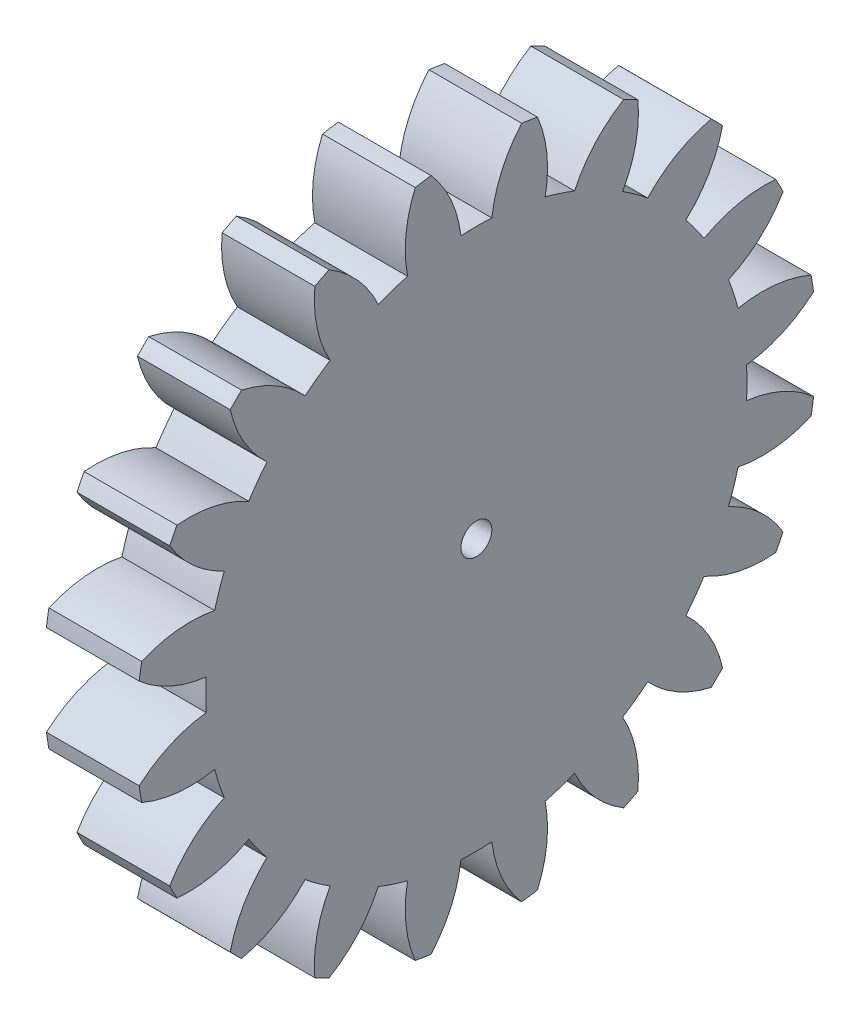
SolidWorks part; units mm, degrees
ref_plane "Plane1" through (0, 0, 0) normal (0, 0, 1) x (1, 0, 0)
ref_plane "Plane2" through (0, 0, 0) normal (0, 1, 0) x (1, 0, 0)
ref_plane "Plane3" through (0, 0, 0) normal (1, 0, 0) x (0, 0, -1)
other "Configuration Table"
sketch "HoldingSke" plane through (0, 0, 0) normal (0, 1, 0) x (1, 0, 0)
  line L0 (0, 0) -> (0.9397, -0.342)
  line L1 (-15, 0) -> (100, 0) construction
  line L2 (0, 0) -> (-2.1039, 2.3779)
  line L3 (0, 0) -> (-11.863, 4.5341)
  line L4 (0, 0) -> (8.1152, 2.9537)
  line L5 (0, 0) -> (-46.8476, -17.4728)
  line L6 (0, 0) -> (-2.4869, -1.6779)
  line L7 (-2.1039, 2.3779) -> (8.6586, 51.2059)
  line L8 (-76.2, 54.61) -> (-76.1, 54.61)
  line L9 (-71.009, 38.7566) -> (-53.1078, 45.2721)
  line L10 (-76.2, 71.12) -> (104.1128, 71.12)
  line L11 (0, 0) -> (-3, 0)
  line L12 (-76.2, 101.6) -> (-76.162, 101.6)
  line L13 (24.9733, 27.94) -> (52.9518, 28.4284)
  line L14 (24.9733, 27.94) -> (24.9743, 27.94)
  line L15 (24.9733, 27.94) -> (100.4006, 29.5858)
  line L16 (-63.627, -1) -> (-12.827, -1)
  circle A0 centre (0, 0) radius 0.5
  circle A1 centre (0, 0) radius 8.749
  circle A2 centre (0, 0) radius 37.5
  circle A3 centre (0, 0) radius 0.5
  dimension "MHD" = 17.498
  dimension "Hub_dia" = 75
  dimension "Bore" = 1
  dimension "MBD" = 1
  dimension "Num_teeth" = 20
  dimension "Pitch" = 1
  dimension "Overall_len" = 50
  dimension "Show_teeth" = 20
  dimension "Thickness" = 3
  dimension "OAL" = 50.0001
  dimension "T_dim" = 0.1
  dimension "Ap" = 20
  dimension "H" = 19.05
  dimension "Pitch_radius" = 180.3128
  dimension "Width" = 3
  dimension "Backlash" = 0.038
  dimension "Addendum_fac" = 1
  dimension "Dedendum_fac" = 1.25
  dimension "Clearance_fac" = 0.25
  dimension "Dedendum_add" = 0.001
  dimension "Module" = 1
sketch "BasProSke" plane through (0, 0, 0) normal (0, 1, 0) x (1, 0, 0)
  line L0 (-10, 0) -> (60, 0) construction
  line L1 (0, 0) -> (0, 11)
  line L2 (0, 0) -> (3, 0)
  line L3 (3, 0) -> (3, 11)
  line L4 (3, 11) -> (0, 11)
  dimension "Thickness" = 3
  dimension "Diameter" = 22
revolve "Base-Revolve" add sketch "BasProSke" angle 360 about L0
sketch "TooCutSke" plane through (0, 0, 0) normal (1, 0, 0) x (0, 0, -1)
  line L1 (0, 0) -> (0, 107) construction
  line L2 (0, 0) -> (-0.8511, 9.9637) construction
  line L3 (0, 0) -> (-3.1206, 19.7028) construction
  line L4 (-0.8511, 9.9637) -> (-1.5603, 9.8514) construction
  arc A0 (0.4999, 8.7347) -> (-0.4999, 8.7347) centre (0, 0) ccw
  arc A1 (1.4852, 10.9249) -> (-1.4852, 10.9249) centre (0, 0) ccw
  circle A2 centre (0, 0) radius 10 construction
  circle A3 centre (0, 0) radius 9.3969 construction
  arc A4 (-0.4999, 8.7347) -> (-1.4852, 10.9249) centre (-4.4722, 8.2645) ccw
  arc A5 (1.4852, 10.9249) -> (0.4999, 8.7347) centre (4.4722, 8.2645) ccw
  dimension "Root_dia" = 17.498
  dimension "Overcut_dia" = 22.0508
  dimension "Pitch_dia" = 20
  dimension "Base_dia" = 18.7939
  dimension "Flank_rad" = 4
  dimension "Half_ang" = 9
  dimension "Half_CT" = 0.7181
extrude "ToothCut" cut sketch "TooCutSke" along normal through all
fillet "Breaks" [suppressed] radius 0.02
fillet "RootFillets" [suppressed] radius 0.251
pattern_circular "TeethCuts" count 20 every 18 about axis through (-10, 0, 0) along (1, 0, 0) of "ToothCut", "RootFillets", "Breaks"
sketch "HubNeaOneSke" plane through (0, 0, 0) normal (-1, 0, 0) x (0, 0, 1)
  circle A0 centre (0, 0) radius 8.749
  dimension "Diameter" = 17.498
extrude "HubNearOne" [suppressed] add sketch "HubNeaOneSke" along normal blind 47.0001
sketch "HubNeaBotSke" plane through (0, 0, 0) normal (-1, 0, 0) x (0, 0, 1)
  circle A0 centre (0, 0) radius 8.749
  dimension "Diameter" = 17.498
extrude "HubNearBoth" [suppressed] add sketch "HubNeaBotSke" along normal blind 23.5
ref_plane "FarPln" through (3, 0, 0) normal (1, 0, 0) x (0, 0, -1)
sketch "HubFarSke" plane through (3, 0, 0) normal (1, 0, 0) x (0, 0, -1)
  circle A0 centre (0, 0) radius 8.749
  dimension "Diameter" = 17.498
extrude "HubFar" [suppressed] add sketch "HubFarSke" along normal blind 23.5
sketch "BorSke" plane through (0, 0, 0) normal (1, 0, 0) x (0, 0, -1)
  circle A0 centre (0, 0) radius 0.5
  dimension "Diameter" = 1
extrude "Bore" cut sketch "BorSke" along normal mid plane 100.0001
sketch "KeySke" plane through (0, 0, 0) normal (1, 0, 0) x (0, 0, -1)
  line L0 (-0.05, 0) -> (-0.05, 0.6)
  line L1 (-0.05, 0.6) -> (0.05, 0.6)
  line L2 (0.05, 0.6) -> (0.05, 0)
  line L3 (0, 0) -> (0, 34) construction
  line L4 (-0.05, 0) -> (0.05, 0)
  dimension "Offset" = 0.6
  dimension "Width" = 0.1
extrude "Keyway" [suppressed] cut sketch "KeySke" along normal mid plane 100.0001
pattern_circular "Keyway2" [suppressed] count 2 every 90 about axis through (-10, 0, 0) along (1, 0, 0)
equation "' \"Module@HoldingSke\" = 6.35"
equation "' \"Num_teeth@HoldingSke\" = 12"
equation "' \"Ap@HoldingSke\" =  20"
equation "' \"Ap@HoldingSke\" = 20"
equation "' \"Width@HoldingSke\" = 0.5 * 25.4"
equation "' \"Hub_dia@HoldingSke\"= 1 * 25.4"
equation "' \"Hub_dia@HoldingSke\" = 1 * 25.4"
equation "' \"Overall_len@HoldingSke\" = 1.0 * 25.4"
equation "' \"Bore@HoldingSke\" = 0.75 * 25.4"
equation "' \"T_dim@HoldingSke\" = 0.1 * 25.4"
equation "' \"Width@KeySke\" = 0.25 * 25.4"
equation "' \"Show_teeth@HoldingSke\" = 13"
equation "' \"Backlash@HoldingSke\" = 0.009 * 25.4"
equation "' \"Addendum_fac@HoldingSke\" = 1.0"
equation "' \"Dedendum_fac@HoldingSke\" = 1.25"
equation "' \"Dedendum_add@HoldingSke\" = 0.00005 * 25.4"
equation "' \"Clearance_fac@HoldingSke\" = 0.25"
equation "\"Pitch@HoldingSke\" = 1 / \"Module@HoldingSke\""
equation "\"Overcut_dia@TooCutSke\" = (\"Num_teeth@HoldingSke\" + 2 * \"Addendum_fac@HoldingSke\") / \"Pitch@HoldingSke\" + 0.002 * 25.4"
equation "\"Pitch_dia@TooCutSke\" = \"Num_teeth@HoldingSke\" / \"Pitch@HoldingSke\""
equation "\"Base_dia@TooCutSke\" = \"Num_teeth@HoldingSke\" / \"Pitch@HoldingSke\" * cos((\"Ap@HoldingSke\"  * 3.14159265 / 180))"
equation "\"Root_dia@TooCutSke\" = (\"Num_teeth@HoldingSke\" + 2) / \"Pitch@HoldingSke\" - 2 * (\"Addendum_fac@HoldingSke\" + \"Dedendum_fac@HoldingSke\") / \"Pitch@HoldingSke\" - \"Dedendum_add@HoldingSke\" * 2"
equation "\"Half_ang@TooCutSke\" = 180 / \"Num_teeth@HoldingSke\""
equation "\"Half_CT@TooCutSke\" = \"Num_teeth@HoldingSke\" / \"Pitch@HoldingSke\" * sin((3.14159265 / 2 / \"Num_teeth@HoldingSke\")) / 2 - 7 * \"Backlash@HoldingSke\" / 4"
equation "\"Flank_rad@TooCutSke\" = \"Num_teeth@HoldingSke\" / \"Pitch@HoldingSke\" / 5"
equation "\"Radius@RootFillets\" = \"Clearance_fac@HoldingSke\" / \"Pitch@HoldingSke\" + \"Dedendum_add@HoldingSke\""
equation "\"Break_rad@Breaks\" = 0.02 / \"Pitch@HoldingSke\""
equation "\"Thickness@HoldingSke\" = \"Width@HoldingSke\""
equation "\"OAL@HoldingSke\" = \"Thickness@HoldingSke\""
equation "\"MHD@HoldingSke\" = (\"Num_teeth@HoldingSke\" + 2) / \"Pitch@HoldingSke\" - 2 * (\"Addendum_fac@HoldingSke\" + \"Dedendum_fac@HoldingSke\")  / \"Pitch@HoldingSke\" - \"Dedendum_add@HoldingSke\" * 2"
equation "\"MBD@HoldingSke\" = (\"Num_teeth@HoldingSke\" + 2) / \"Pitch@HoldingSke\" - 2 * (\"Addendum_fac@HoldingSke\" + \"Dedendum_fac@HoldingSke\")  / \"Pitch@HoldingSke\" - \"Dedendum_add@HoldingSke\" * 2 - 0.002 * 25.4"
equation "\"MHD@HoldingSke\" = ((sgn( \"MHD@HoldingSke\" - \"Hub_dia@HoldingSke\" )-1)*( \"MHD@HoldingSke\" - \"Hub_dia@HoldingSke\" ))/-2+ \"Hub_dia@HoldingSke\""
equation "\"MBD@HoldingSke\" = ((sgn( \"MBD@HoldingSke\" - \"Bore@HoldingSke\" )-1)*( \"MBD@HoldingSke\" - \"Bore@HoldingSke\" ))/-2+ \"Bore@HoldingSke\""
equation "\"OAL@HoldingSke\" = ((sgn( \"OAL@HoldingSke\" - \"Overall_len@HoldingSke\" )+1)*( \"OAL@HoldingSke\" - \"Overall_len@HoldingSke\" ))/2 + \"Overall_len@HoldingSke\" + 0.000002 * 25.4"
equation "\"Num_teeth@TeethCuts\" = int( \"Show_teeth@HoldingSke\" ) + 1"
equation "\"Num_teeth@TeethCuts\" = ((sgn( \"Num_teeth@TeethCuts\" - \"Num_teeth@HoldingSke\" )-1)*( \"Num_teeth@TeethCuts\" - \"Num_teeth@HoldingSke\" ))/-2+ \"Num_teeth@HoldingSke\""
equation "\"Num_teeth@TeethCuts\" = ((sgn( \"Num_teeth@TeethCuts\" - 2.0)+1)*( \"Num_teeth@TeethCuts\" - 2.0))/2 +2.0"
equation "\"Angle@TeethCuts\" = 360.0 / \"Num_teeth@HoldingSke\""
equation "\"Diameter@BasProSke\" = (\"Num_teeth@HoldingSke\" + 2 * \"Addendum_fac@HoldingSke\") / \"Pitch@HoldingSke\""
equation "\"Thickness@BasProSke\"  = \"Thickness@HoldingSke\""
equation "' \"Fillet_rad@BasProSke\" =  \"Thickness@HoldingSke\" * 0.05"
equation "' \"Fillet_rad@BasProSke\" = \"Thickness@HoldingSke\" * 0.05"
equation "\"MHD@HoldingSke\" = ((sgn( \"MHD@HoldingSke\" - \"Root_dia@TooCutSke\" )-1)*( \"MHD@HoldingSke\" - \"Root_dia@TooCutSke\" ))/-2+ \"Root_dia@TooCutSke\""
equation "\"Diameter@HubNeaOneSke\" = \"MHD@HoldingSke\""
equation "\"Length@HubNearOne\" = \"OAL@HoldingSke\" - \"Thickness@BasProSke\""
equation "\"Diameter@HubNeaBotSke\" = \"MHD@HoldingSke\""
equation "\"Length@HubNearBoth\" = ( \"OAL@HoldingSke\" - \"Thickness@BasProSke\" ) / 2.0"
equation "\"Thickness@FarPln\" = \"Thickness@BasProSke\""
equation "\"Diameter@HubFarSke\" = \"MHD@HoldingSke\""
equation "\"Length@HubFar\" = ( \"OAL@HoldingSke\" - \"Thickness@BasProSke\" ) / 2.0"
equation "\"Diameter@BorSke\" = \"MBD@HoldingSke\""
equation "\"D1@Bore\" = \"OAL@HoldingSke\" * 2.0"
equation "\"D1@Keyway\" = \"OAL@HoldingSke\" * 2.0"
equation "\"Offset@KeySke\" = \"T_dim@HoldingSke\" + \"MBD@HoldingSke\" / 2.0"
